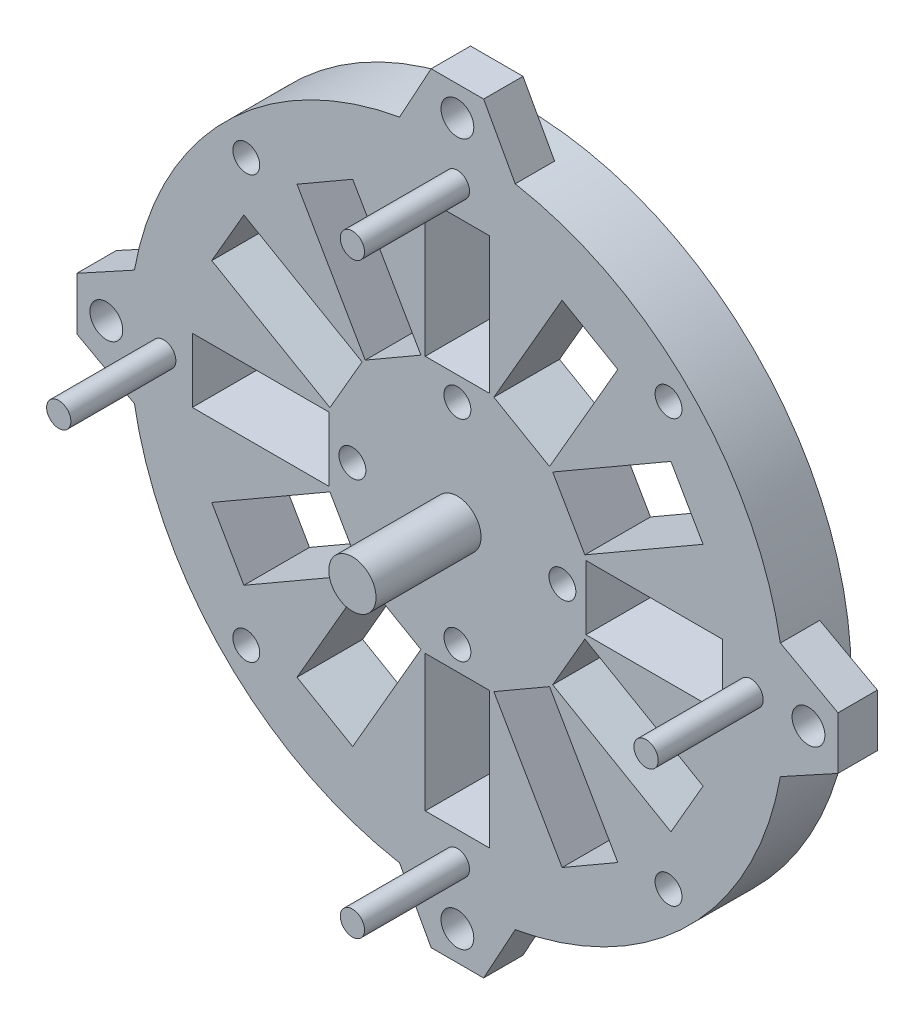
SolidWorks part; units mm, degrees
ref_plane "Alzado" through (0, 0, 0) normal (1, 0, 0) x (0, 1, 0)
ref_plane "Planta" through (0, 0, 0) normal (0, 0, 1) x (0, 1, 0)
ref_plane "Vista lateral" through (0, 0, 0) normal (0, 1, 0) x (-1, 0, 0)
sketch "Croquis1" plane through (0, 0, 0) normal (0, 0, 1) x (0, 1, 0)
  line L5 (15.9565, 37.4374) -> (5.5565, 19.4241)
  line L6 (-4.9, 40.4) -> (4.9, 40.4)
  line L75 (-4.9, 40.4) -> (-4.9, 19.6)
  line L76 (-4.9, 19.6) -> (4.9, 19.6)
  line L77 (4.9, 40.4) -> (4.9, 19.6)
  line L78 (-4.9, 40.4) -> (4.9, 19.6) construction
  line L79 (-4.9, 19.6) -> (4.9, 40.4) construction
  line L80 (15.9565, 37.4374) -> (24.4435, 32.5374)
  line L81 (24.4435, 32.5374) -> (14.0435, 14.5241)
  line L82 (5.5565, 19.4241) -> (14.0435, 14.5241)
  line L83 (32.5374, 24.4435) -> (14.5241, 14.0435)
  line L84 (32.5374, 24.4435) -> (37.4374, 15.9565)
  line L85 (37.4374, 15.9565) -> (19.4241, 5.5565)
  line L86 (14.5241, 14.0435) -> (19.4241, 5.5565)
  line L87 (40.4, 4.9) -> (19.6, 4.9)
  line L88 (40.4, 4.9) -> (40.4, -4.9)
  line L89 (40.4, -4.9) -> (19.6, -4.9)
  line L90 (19.6, 4.9) -> (19.6, -4.9)
  line L91 (37.4374, -15.9565) -> (19.4241, -5.5565)
  line L92 (37.4374, -15.9565) -> (32.5374, -24.4435)
  line L93 (32.5374, -24.4435) -> (14.5241, -14.0435)
  line L94 (19.4241, -5.5565) -> (14.5241, -14.0435)
  line L95 (24.4435, -32.5374) -> (14.0435, -14.5241)
  line L96 (24.4435, -32.5374) -> (15.9565, -37.4374)
  line L97 (15.9565, -37.4374) -> (5.5565, -19.4241)
  line L98 (14.0435, -14.5241) -> (5.5565, -19.4241)
  line L99 (4.9, -40.4) -> (4.9, -19.6)
  line L100 (4.9, -40.4) -> (-4.9, -40.4)
  line L101 (-4.9, -40.4) -> (-4.9, -19.6)
  line L102 (4.9, -19.6) -> (-4.9, -19.6)
  line L103 (-15.9565, -37.4374) -> (-5.5565, -19.4241)
  line L104 (-15.9565, -37.4374) -> (-24.4435, -32.5374)
  line L105 (-24.4435, -32.5374) -> (-14.0435, -14.5241)
  line L106 (-5.5565, -19.4241) -> (-14.0435, -14.5241)
  line L107 (-32.5374, -24.4435) -> (-14.5241, -14.0435)
  line L108 (-32.5374, -24.4435) -> (-37.4374, -15.9565)
  line L109 (-37.4374, -15.9565) -> (-19.4241, -5.5565)
  line L110 (-14.5241, -14.0435) -> (-19.4241, -5.5565)
  line L111 (-40.4, -4.9) -> (-19.6, -4.9)
  line L112 (-40.4, -4.9) -> (-40.4, 4.9)
  line L113 (-40.4, 4.9) -> (-19.6, 4.9)
  line L114 (-19.6, -4.9) -> (-19.6, 4.9)
  line L115 (-37.4374, 15.9565) -> (-19.4241, 5.5565)
  line L116 (-37.4374, 15.9565) -> (-32.5374, 24.4435)
  line L117 (-32.5374, 24.4435) -> (-14.5241, 14.0435)
  line L118 (-19.4241, 5.5565) -> (-14.5241, 14.0435)
  line L119 (-24.4435, 32.5374) -> (-14.0435, 14.5241)
  line L120 (-24.4435, 32.5374) -> (-15.9565, 37.4374)
  line L121 (-15.9565, 37.4374) -> (-5.5565, 19.4241)
  line L122 (-14.0435, 14.5241) -> (-5.5565, 19.4241)
  point P0 (0, 30)
  point P51 (0, 0)
  dimension "D5" = 12
  dimension "D6" = 30
  dimension "D1" = 9.8
  dimension "D2" = 20.8
  dimension "D3" = 0
  dimension "D4" = 30
sketch "Croquis2" plane through (0, 0, 0) normal (0, 0, 1) x (0, 1, 0)
  circle A0 centre (0, 0) radius 50
extrude "Saliente-Extruir1" add sketch "Croquis2" along normal blind 10
extrude "Cortar-Extruir3" cut sketch "Croquis1" along normal through all
sketch "Croquis4" plane through (0, 0, 10) normal (0, 0, 1) x (1, 0, 0)
  circle A0 centre (0, 0) radius 3.6
  dimension "D1" = 7.2
extrude "Saliente-Extruir2" add sketch "Croquis4" along normal blind 16
sketch "Croquis5" plane through (0, 0, 10) normal (0, 0, 1) x (1, 0, 0)
  circle A0 centre (0, 44.75) radius 1.85
  circle A1 centre (44.75, 0) radius 1.85
  circle A2 centre (0, -44.75) radius 1.85
  circle A3 centre (-44.75, 0) radius 1.85
  point P15 (0, 0)
  dimension "D2" = 3.7
  dimension "D1" = 44.75
  dimension "D3" = 4
extrude "Saliente-Extruir3" add sketch "Croquis5" along normal blind 16
sketch "Croquis7" plane through (0, 0, 10) normal (0, 0, 1) x (1, 0, 0)
  line L0 (4, 58) -> (8.8125, 49.2173)
  line L1 (-4, 58) -> (4, 58)
  line L5 (58, 4) -> (49.2173, 8.8125)
  line L6 (58, 4) -> (58, -4)
  line L7 (-4, 58) -> (-8.8125, 49.2173)
  line L8 (58, -4) -> (49.2173, -8.8125)
  line L9 (4, -58) -> (8.8125, -49.2173)
  line L10 (4, -58) -> (-4, -58)
  line L11 (-4, -58) -> (-8.8125, -49.2173)
  line L12 (-58, -4) -> (-49.2173, -8.8125)
  line L13 (-58, -4) -> (-58, 4)
  line L14 (-58, 4) -> (-49.2173, 8.8125)
  circle A0 centre (0, 0) radius 50 construction
  arc A1 (8.8125, 49.2173) -> (-8.8125, 49.2173) centre (0, 0) ccw
  arc A2 (49.2173, -8.8125) -> (49.2173, 8.8125) centre (0, 0) ccw
  arc A3 (-8.8125, -49.2173) -> (8.8125, -49.2173) centre (0, 0) ccw
  arc A4 (-49.2173, 8.8125) -> (-49.2173, -8.8125) centre (0, 0) ccw
  point P0 (0, 50)
  point P24 (0, 0)
  dimension "D1" = 8
  dimension "D2" = 4
extrude "Saliente-Extruir4" add sketch "Croquis7" against normal blind 6
sketch "Croquis8" plane through (0, 0, 10) normal (0, 0, 1) x (1, 0, 0)
  line L0 (4, 58) -> (-4, 58) construction
  line L1 (58, -4) -> (58, 4) construction
  line L2 (-4, -58) -> (4, -58) construction
  line L3 (-58, 4) -> (-58, -4) construction
  circle A0 centre (0, 53.5) radius 2.5
  circle A1 centre (53.5, 0) radius 2.5
  circle A2 centre (0, -53.5) radius 2.5
  circle A3 centre (-53.5, 0) radius 2.5
  point P13 (0, 0)
  dimension "D1" = 4.5
  dimension "5.1" = 5
  dimension "D6" = 4.5
  dimension "D3" = 0
  dimension "D4" = 4.5
  dimension "D5" = 4.5
  dimension "D2" = 4
extrude "Cortar-Extruir4" cut sketch "Croquis8" against normal blind 6.5
cosmetic thread "Rosca cosmética9" parameters "D2"=5
cosmetic thread "Rosca cosmética10" parameters "D2"=5
cosmetic thread "Rosca cosmética11" parameters "D2"=5
cosmetic thread "Rosca cosmética12" parameters "D2"=5
sketch "Croquis9" plane through (0, 0, 10) normal (0, 0, 1) x (1, 0, 0)
  circle A0 centre (0, 16) radius 2.05
  circle A1 centre (16, 0) radius 2.05
  circle A2 centre (0, -16) radius 2.05
  circle A3 centre (-16, 0) radius 2.05
  circle A4 centre (-32.1734, 32.1734) radius 2.05
  circle A5 centre (32.1734, 32.1734) radius 2.05
  circle A6 centre (32.1734, -32.1734) radius 2.05
  circle A7 centre (-32.1734, -32.1734) radius 2.05
  point P12 (0, 0)
  point P21 (0, 0)
  dimension "D1" = 4.1
  dimension "D4" = 4.1
  dimension "D2" = 16
  dimension "D5" = 45.5
  dimension "D3" = 4
  dimension "D6" = 4
extrude "Cortar-Extruir5" cut sketch "Croquis9" against normal blind 6
cosmetic thread "Rosca cosmética1" parameters "D2"=5
cosmetic thread "Rosca cosmética2" parameters "D2"=5
cosmetic thread "Rosca cosmética3" parameters "D2"=5
cosmetic thread "Rosca cosmética4" parameters "D2"=5
cosmetic thread "Rosca cosmética5" parameters "D2"=5
cosmetic thread "Rosca cosmética6" parameters "D2"=5
cosmetic thread "Rosca cosmética7" parameters "D2"=5
cosmetic thread "Rosca cosmética8" parameters "D2"=5
